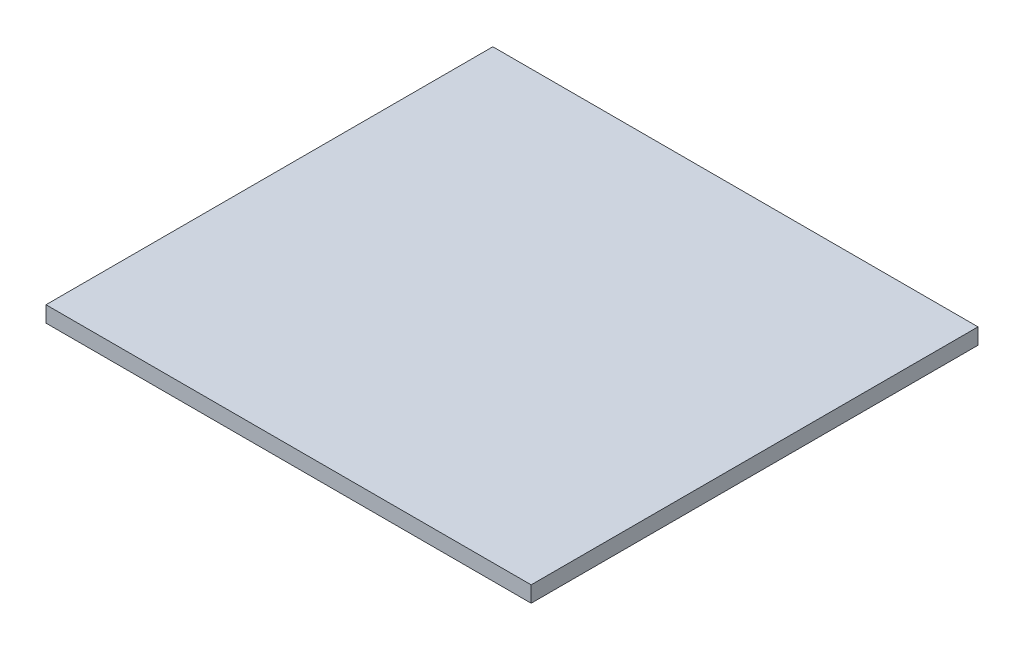
SolidWorks part; units mm, degrees
ref_plane "Front Plane" through (0, 0, 0) normal (0, 0, 1) x (1, 0, 0)
ref_plane "Top Plane" through (0, 0, 0) normal (0, 1, 0) x (1, 0, 0)
ref_plane "Right Plane" through (0, 0, 0) normal (1, 0, 0) x (0, 0, -1)
sketch "Sketch1" plane through (0, 0, 0) normal (0, 1, 0) x (1, 0, 0)
  line L1 (0, 0) -> (96.52, 0)
  line L2 (0, 0) -> (0, 88.9)
  line L3 (0, 88.9) -> (96.52, 88.9)
  line L4 (96.52, 0) -> (96.52, 88.9)
  dimension "D1" = 88.9
  dimension "D2" = 96.52
extrude "Boss-Extrude1" add sketch "Sketch1" along normal blind 3.175
